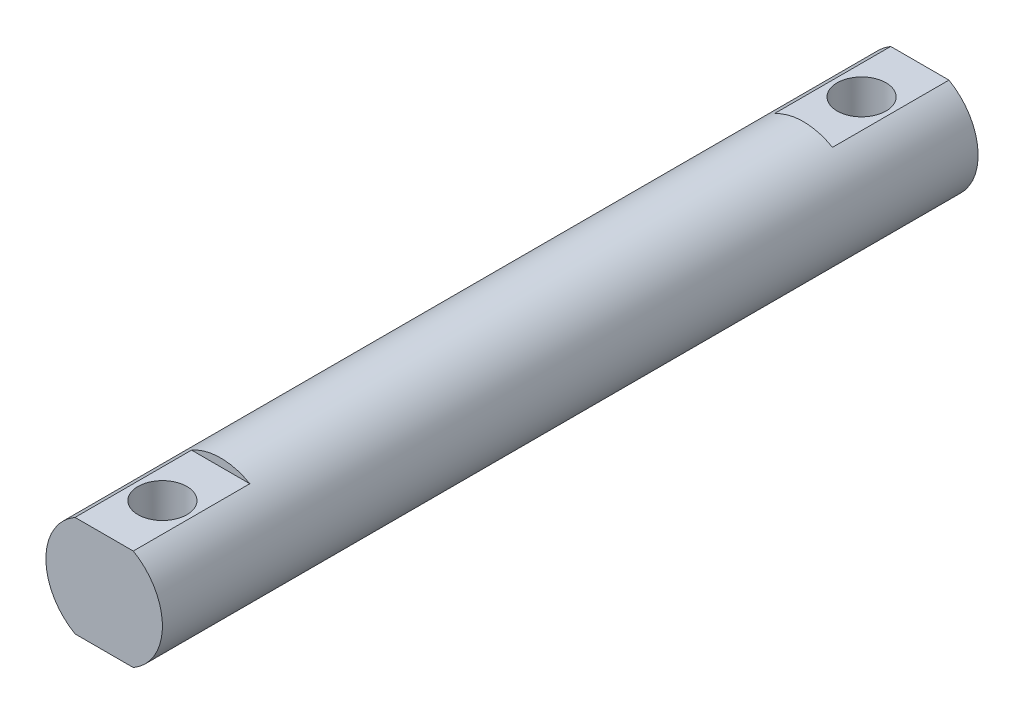
SolidWorks part; units mm, degrees
ref_plane "前视基准面" through (0, 0, 0) normal (0, 0, 1) x (1, 0, 0)
ref_plane "上视基准面" through (0, 0, 0) normal (0, 1, 0) x (1, 0, 0)
ref_plane "右视基准面" through (0, 0, 0) normal (1, 0, 0) x (0, 0, -1)
other "Configuration Table"
sketch "草图1" plane through (0, 0, 0) normal (0, 0, 1) x (1, 0, 0)
  circle A0 centre (0, 0) radius 5
  dimension "D1" = 10
extrude "凸台-拉伸1" add sketch "草图1" along normal blind 70
sketch "草图2" plane through (0, 0, 0) normal (0, 1, 0) x (1, 0, 0)
  line L0 (-5, -35) -> (5, -35) construction
  line L1 (-5, 0) -> (-5, -70) construction
  line L2 (5, -70) -> (5, 0) construction
  line L3 (0, -5) -> (0, 0) construction
  line L4 (0, -65) -> (0, -70) construction
  line L5 (5, 0) -> (-5, 0) construction
  circle A0 centre (0, -5) radius 2.1
  circle A1 centre (0, -65) radius 2.1
  dimension "D1" = 4.2
  dimension "D2" = 5
extrude "切除-拉伸1" cut sketch "草图2" against normal mid plane 10
sketch "草图3" plane through (0, 0, 70) normal (0, 0, 1) x (1, 0, 0)
  line L0 (-2.5, 4.3301) -> (2.5, 4.3301)
  line L1 (2.5, 4.3301) -> (2.5, 14.3301)
  line L2 (2.5, 14.3301) -> (-2.5, 14.3301)
  line L3 (-2.5, 14.3301) -> (-2.5, 4.3301)
  line L4 (0, 0) -> (5, 0) construction
  line L5 (-2.5, -14.3301) -> (-2.5, -4.3301)
  line L6 (2.5, -14.3301) -> (-2.5, -14.3301)
  line L7 (2.5, -4.3301) -> (2.5, -14.3301)
  line L8 (-2.5, -4.3301) -> (2.5, -4.3301)
  circle A0 centre (0, 0) radius 5 construction
  dimension "D1" = 5
  dimension "D2" = 10
extrude "切除-拉伸2" cut sketch "草图3" against normal blind 10
sketch "草图4" plane through (0, 0, 0) normal (0, 0, -1) x (-1, 0, 0)
  line L0 (0, 0) -> (5, 0) construction
  line L1 (-2.5, 14.3301) -> (2.5, 14.3301)
  line L2 (-2.5, 14.3301) -> (-2.5, 4.3301)
  line L3 (-2.5, 4.3301) -> (2.5, 4.3301)
  line L4 (2.5, 14.3301) -> (2.5, 4.3301)
  line L5 (2.5, -14.3301) -> (2.5, -4.3301)
  line L6 (-2.5, -4.3301) -> (2.5, -4.3301)
  line L7 (-2.5, -14.3301) -> (-2.5, -4.3301)
  line L8 (-2.5, -14.3301) -> (2.5, -14.3301)
  circle A0 centre (0, 0) radius 5 construction
  dimension "D1" = 10
  dimension "D2" = 5
extrude "切除-拉伸3" cut sketch "草图4" against normal blind 10
